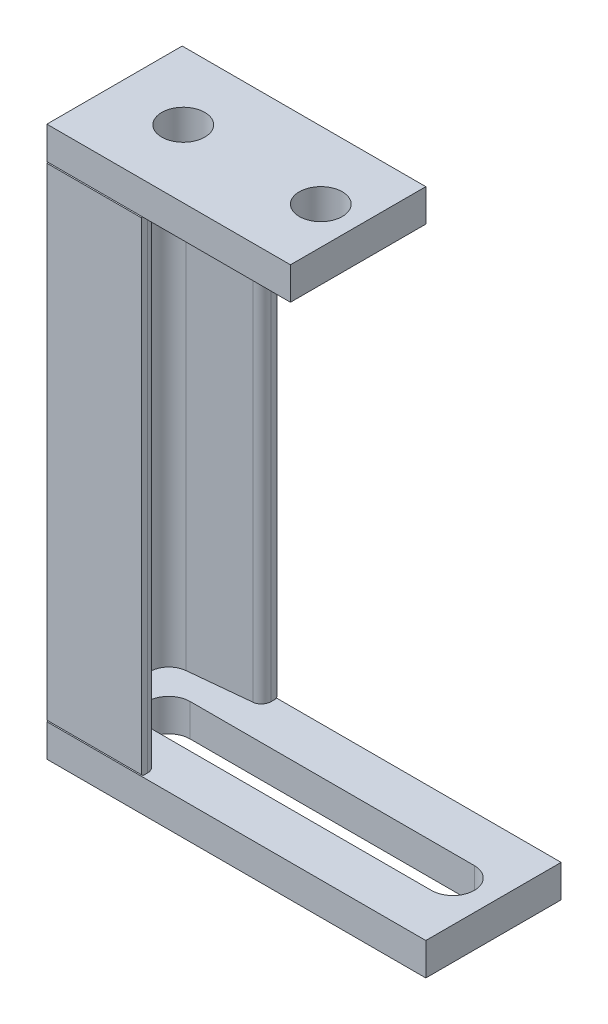
SolidWorks part; units mm, degrees
ref_plane "Front Plane" through (0, 0, 0) normal (0, 0, 1) x (1, 0, 0)
ref_plane "Top Plane" through (0, 0, 0) normal (0, 1, 0) x (1, 0, 0)
ref_plane "Right Plane" through (0, 0, 0) normal (1, 0, 0) x (0, 0, -1)
ref_plane "Plane1" through (0, 179.2, 0) normal (0, -1, 0) x (1, 0, 0)
sketch "Sketch1" plane through (0, 179.2, 0) normal (0, -1, 0) x (1, 0, 0)
  line L0 (0, 25) -> (0, -25)
  line L1 (0, -25) -> (90, -25)
  line L2 (90, -25) -> (90, 25)
  line L3 (90, 25) -> (0, 25)
extrude "Boss-Extrude1" add sketch "Sketch1" against normal blind 12
ref_plane "Plane2" through (0, 0, 0) normal (-1, 0, 0) x (0, -1, 0)
sketch "Sketch2" plane through (0, 0, 0) normal (-1, 0, 0) x (0, -1, 0)
  line L0 (-0.5, -25) -> (0, -24.5)
  line L1 (0, -24.5) -> (0, -25)
  line L2 (0, -25) -> (12, -25)
  line L3 (12, -25) -> (12, 25)
  line L4 (12, 25) -> (0, 25)
  line L5 (0, 25) -> (0, 24.5)
  line L6 (0, 24.5) -> (-0.5, 25)
  line L7 (-0.5, 25) -> (-178.7, 25)
  line L8 (-178.7, 25) -> (-179.2, 24.5)
  line L9 (-179.2, 24.5) -> (-179.2, -24.5)
  line L10 (-179.2, -24.5) -> (-178.7, -25)
  line L11 (-178.7, -25) -> (-0.5, -25)
extrude "Boss-Extrude2" add sketch "Sketch2" against normal blind 35
sketch "Sketch3" plane through (35, 0, 0) normal (1, 0, 0) x (0, 0, -1)
  line L0 (-25, -12) -> (-25, 0)
  line L1 (-25, 0) -> (25, 0)
  line L2 (25, 0) -> (25, -12)
  line L3 (25, -12) -> (-25, -12)
extrude "Boss-Extrude3" add sketch "Sketch3" along normal blind 105
sketch "Sketch4" plane through (35, 0, 0) normal (1, 0, 0) x (0, 0, -1)
  line L0 (-16.4279, 0) -> (16.4279, 0)
  line L1 (16.4279, 0) -> (16.4279, 179.2)
  line L2 (16.4279, 179.2) -> (-16.4279, 179.2)
  line L3 (-16.4279, 179.2) -> (-16.4279, 0)
extrude "Cut-Extrude1" cut sketch "Sketch4" against normal blind 32
sketch "Sketch5" plane through (0, -12, 0) normal (0, -1, 0) x (1, 0, 0)
  line L0 (125, 7.94) -> (20, 7.94)
  line L1 (20, -7.94) -> (125, -7.94)
  arc A0 (20, 7.94) -> (20, -7.94) centre (20, 0) ccw
  arc A1 (125, -7.94) -> (125, 7.94) centre (125, 0) ccw
extrude "Cut-Extrude2" cut sketch "Sketch5" against normal up to next
draft "Draft1" type of draft neutral plane draft angle 5.7 faces to draft 2 face at (19, 89.6, -16.4279) face at (19, 89.6, 16.4279) neutral plane through (3, 0, 0) neutral plane normal (1, 0, 0) parameters "D1"=5.7
hole_wizard "M13 Clearance Hole1" positions "Sketch7" profile "Sketch6" hole size "M13" standard "ANSI Metric"
sketch "Sketch7" plane through (3, 0, 0) normal (1, 0, 0) x (0, 0, -1)
  point P0 (0, 38.8)
sketch "Sketch6" plane through (3, 38.8, 0) normal (0, 1, 0) x (0, 0, -1)
  line L0 (0, 0) -> (0, 3.0001)
  line L1 (0, 3.0001) -> (7.94, 3.0001)
  line L2 (7.94, 3.0001) -> (7.94, 0)
  line L5 (7.94, 0) -> (0, 0)
  line L11 (0, -6.35) -> (0, 107.95) construction
  dimension "Thru Hole Dia." = 15.88
  dimension "Thru Hole Depth" = 3.0001
hole_wizard "M13 Clearance Hole2" positions "Sketch9" profile "Sketch8" hole size "M13" standard "ANSI Metric"
sketch "Sketch9" plane through (0, 0, 0) normal (-1, 0, 0) x (0, 0, 1)
  point P0 (0, 89.6)
  point P1 (0, 115)
  point P2 (0, 140.4)
  point P3 (0, 165.8)
sketch "Sketch8" plane through (0, 89.6, 0) normal (0, 1, 0) x (0, 0, 1)
  line L0 (0, 0) -> (0, 140)
  line L1 (0, 140) -> (7.94, 140)
  line L2 (7.94, 140) -> (7.94, 0)
  line L5 (7.94, 0) -> (0, 0)
  line L11 (0, -6.35) -> (0, 107.95) construction
  dimension "Thru Hole Dia." = 15.88
  dimension "Thru Hole Depth" = 140
hole_wizard "M13 Clearance Hole3" positions "Sketch11" profile "Sketch10" hole size "M13" standard "ANSI Metric"
sketch "Sketch11" plane through (0, 179.2, 0) normal (0, -1, 0) x (-1, 0, 0)
  point P0 (-76.2, 0)
  point P1 (-25.4, 0)
sketch "Sketch10" plane through (76.2, 179.2, 0) normal (1, 0, 0) x (0, 0, -1)
  line L0 (0, 0) -> (0, 12)
  line L1 (0, 12) -> (7.94, 12)
  line L2 (7.94, 12) -> (7.94, 0)
  line L5 (7.94, 0) -> (0, 0)
  line L11 (0, -6.35) -> (0, 107.95) construction
  dimension "Thru Hole Dia." = 15.88
  dimension "Thru Hole Depth" = 12
fillet "Fillet1" radius 3.5 2 edges at (35, 89.6, 19.622) (35, 89.6, -19.622)
fillet "Fillet2" radius 7 2 edges at (3, 89.6, -16.4279) (3, 89.6, 16.4279)
